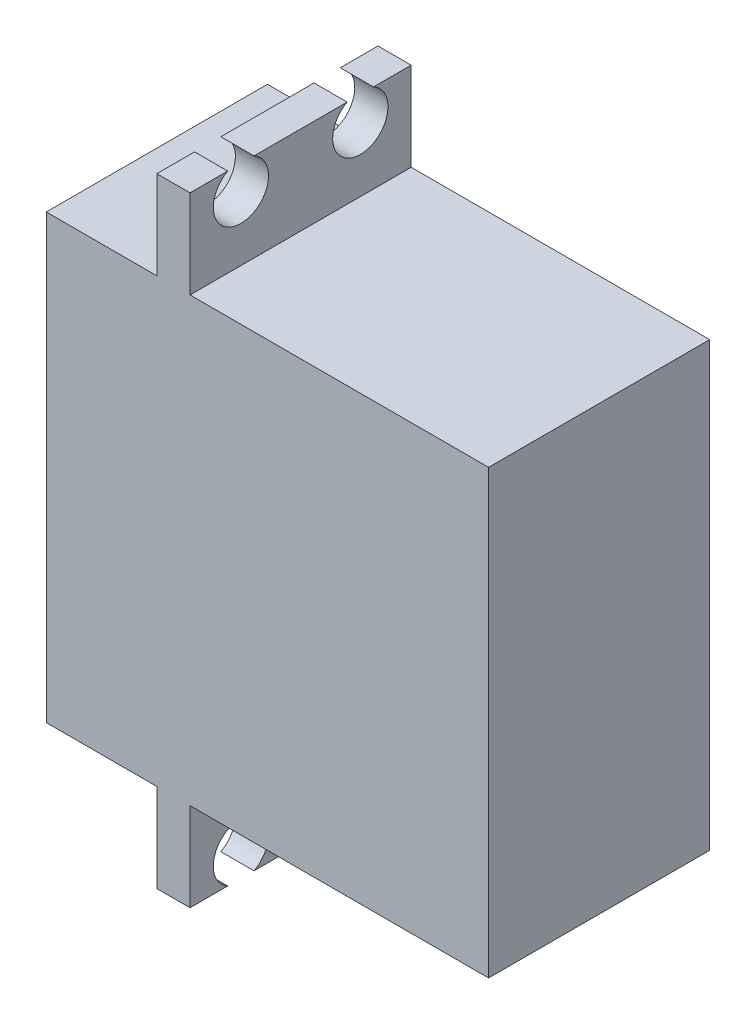
SolidWorks part; units mm, degrees
ref_plane "Plan de face" through (0, 0, 0) normal (0, 0, 1) x (1, 0, 0)
ref_plane "Plan de dessus" through (0, 0, 0) normal (0, 1, 0) x (1, 0, 0)
ref_plane "Plan de droite" through (0, 0, 0) normal (1, 0, 0) x (0, 0, -1)
sketch "Esquisse1" plane through (0, 0, 0) normal (0, 0, 1) x (1, 0, 0)
  line L1 (-20, -20) -> (20, -20)
  line L2 (-20, -20) -> (-20, 20)
  line L3 (-20, 20) -> (20, 20)
  line L4 (20, -20) -> (20, 20)
  line L5 (-20, -20) -> (20, 20) construction
  line L6 (-20, 20) -> (20, -20) construction
  point P0 (0, 0)
  dimension "D1" = 40
  dimension "D2" = 40
extrude "Boss.-Extru.1" add sketch "Esquisse1" along normal blind 20
sketch "Esquisse2" plane through (0, 20, 0) normal (0, 1, 0) x (1, 0, 0)
  line L0 (-20, 0) -> (-10, 0) construction
  line L1 (20, 0) -> (-20, 0) construction
  line L2 (20, -20) -> (-20, -20) construction
  line L3 (-10, 0) -> (-7, 0)
  line L4 (-10, 0) -> (-10, -20)
  line L5 (-10, -20) -> (-7, -20)
  line L6 (-7, 0) -> (-7, -20)
  dimension "D1" = 10
  dimension "D2" = 3
extrude "Boss.-Extru.2" add sketch "Esquisse2" along normal blind 8
sketch "Esquisse3" plane through (0, -20, 0) normal (0, -1, 0) x (1, 0, 0)
  line L0 (-20, 20) -> (-10, 20) construction
  line L1 (-20, 20) -> (20, 20) construction
  line L2 (-20, 0) -> (20, 0) construction
  line L3 (-10, 20) -> (-7, 20)
  line L4 (-10, 20) -> (-10, 0)
  line L5 (-10, 0) -> (-7, 0)
  line L6 (-7, 20) -> (-7, 0)
  dimension "D1" = 10
  dimension "D2" = 3
extrude "Boss.-Extru.4" add sketch "Esquisse3" along normal blind 8
sketch "Esquisse5" plane through (-10, 0, 0) normal (-1, 0, 0) x (0, 0, 1)
  line L1 (20, -20) -> (0, -20) construction
  line L2 (0, -28) -> (0, -20) construction
  line L3 (20, -28) -> (20, -20) construction
  circle A0 centre (4.6, -25.8) radius 2.5
  circle A1 centre (15.4, -25.8) radius 2.5
  point P4 (0, 0)
  point P5 (17.0894, -26.435)
  dimension "D1" = 5
  dimension "D3" = 4.6
  dimension "D4" = 4.6
  dimension "D2" = 5.8
extrude "Enlèv. mat.-Extru.9" cut sketch "Esquisse5" against normal blind 8 contours A0 | A1
sketch "Esquisse6" plane through (-10, 0, 0) normal (-1, 0, 0) x (0, 0, 1)
  line L0 (20, 20) -> (0, 20) construction
  line L1 (0, 28) -> (0, 20) construction
  line L2 (20, 28) -> (20, 20) construction
  circle A0 centre (4.6, 25.8) radius 2.5
  circle A1 centre (15.4, 25.8) radius 2.5
  point P4 (0, 0)
  dimension "D1" = 5
  dimension "D2" = 5.8
  dimension "D3" = 4.6
  dimension "D4" = 4.6
extrude "Enlèv. mat.-Extru.10" cut sketch "Esquisse6" against normal blind 8
sketch "Esquisse7" plane through (-20, 0, 0) normal (-1, 0, 0) x (0, 0, 1)
  line L0 (20, 20) -> (20, -20) construction
  line L1 (0, 20) -> (20, 20) construction
  circle A0 centre (10, 10) radius 2.95
  dimension "D1" = 5.9
  dimension "D3" = 10
  dimension "D2" = 10
extrude "Boss.-Extru.5" add sketch "Esquisse7" along normal blind 5
